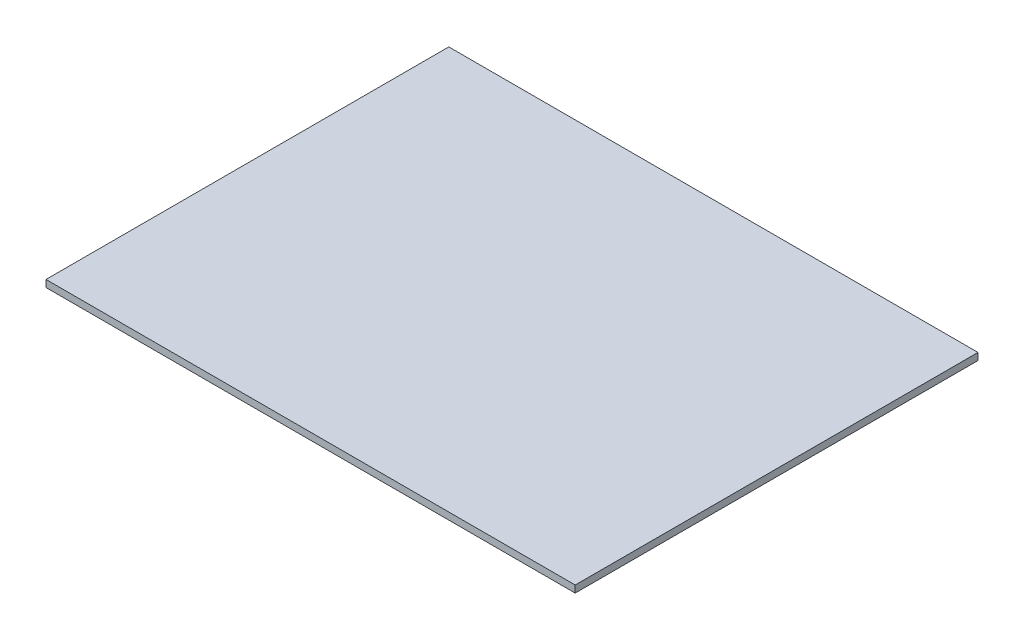
SolidWorks part; units mm, degrees
ref_plane "Front Plane" through (0, 0, 0) normal (0, 0, 1) x (1, 0, 0)
ref_plane "Top Plane" through (0, 0, 0) normal (0, 1, 0) x (1, 0, 0)
ref_plane "Right Plane" through (0, 0, 0) normal (1, 0, 0) x (0, 0, -1)
sketch "Sketch1" plane through (0, 0, 0) normal (0, 1, 0) x (1, 0, 0)
  line L5 (-75.35, 57.35) -> (75.35, 57.35)
  line L6 (-75.35, 57.35) -> (-75.35, -57.35)
  line L7 (-75.35, -57.35) -> (75.35, -57.35)
  line L8 (75.35, 57.35) -> (75.35, -57.35)
  line L9 (-75.35, 57.35) -> (75.35, -57.35) construction
  line L10 (-75.35, -57.35) -> (75.35, 57.35) construction
  point P0 (0, 0)
  dimension "D1" = 150.7
  dimension "D2" = 114.7
extrude "Boss-Extrude1" add sketch "Sketch1" along normal blind 2
